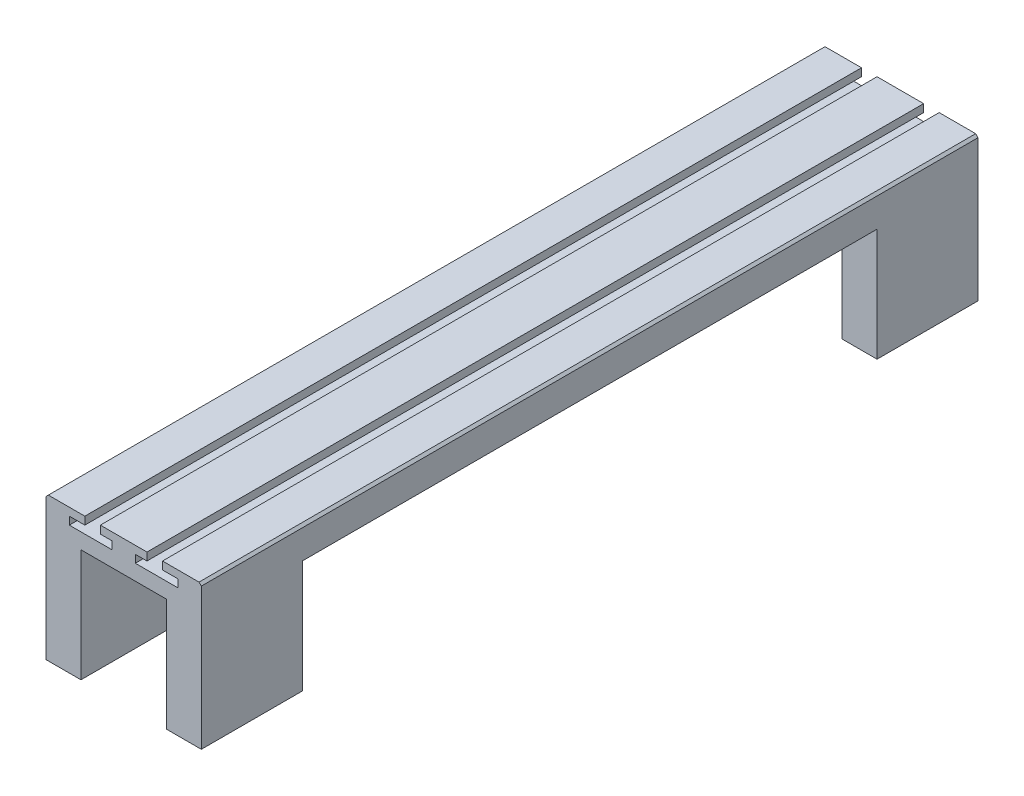
SolidWorks part; units mm, degrees
ref_plane "Front Plane" through (0, 0, 0) normal (0, 0, 1) x (1, 0, 0)
ref_plane "Top Plane" through (0, 0, 0) normal (0, 1, 0) x (1, 0, 0)
ref_plane "Right Plane" through (0, 0, 0) normal (1, 0, 0) x (0, 0, -1)
sketch "Sketch1" plane through (0, 0, 0) normal (0, 0, 1) x (1, 0, 0)
  line L0 (-8.5485, 0) -> (-50, 0)
  line L1 (-50, 0) -> (-50, -40)
  line L2 (-50, -40) -> (150, -40)
  line L3 (150, -40) -> (150, 0)
  line L4 (150, 0) -> (131.4515, 0)
  line L5 (120, -10) -> (120, -20)
  line L6 (120, -20) -> (65, -20)
  line L7 (65, -20) -> (65, -10)
  line L8 (77.4286, 0) -> (47.4286, 0)
  line L9 (35, -10) -> (35, -20)
  line L10 (35, -20) -> (-20, -20)
  line L11 (-20, -20) -> (-20, -10)
  line L12 (131.4515, 0) -> (100, 0)
  line L13 (100, 0) -> (100, -10)
  line L14 (100, -10) -> (120, -10)
  line L15 (77.4286, 0) -> (80, 0)
  line L16 (80, 0) -> (80, -10)
  line L17 (80, -10) -> (65, -10)
  line L18 (47.4286, 0) -> (20, 0)
  line L19 (20, 0) -> (20, -10)
  line L20 (20, -10) -> (35, -10)
  line L21 (-8.5485, 0) -> (0, 0)
  line L22 (0, 0) -> (0, -10)
  line L23 (0, -10) -> (-20, -10)
  line L24 (50, -40) -> (50, 39.4571) construction
  dimension "D1" = 200
  dimension "D2" = 40
  dimension "D3" = 20
  dimension "D4" = 50
  dimension "D5" = 60
  dimension "D6" = 50
  dimension "D7" = 20
  dimension "D8" = 30
  dimension "D9" = 30
  dimension "D10" = 30
  dimension "D11" = 15
  dimension "D12" = 10
extrude "Boss-Extrude1" add sketch "Sketch1" along normal blind 1000
sketch "Sketch2" plane through (0, -40, 0) normal (0, -1, 0) x (1, 0, 0)
  line L0 (50, 1000) -> (50, 0) construction
  line L1 (-50, 1000) -> (150, 1000) construction
  line L2 (-50, 0) -> (150, 0) construction
  line L3 (-50, 500) -> (150, 500) construction
  line L4 (-50, 1000) -> (-50, 0) construction
  line L5 (150, 1000) -> (150, 0) construction
  line L6 (105, 1000) -> (105, 870)
  line L7 (-50, 1000) -> (-5, 1000)
  line L8 (-50, 1000) -> (-50, 870)
  line L9 (-50, 870) -> (-5, 870)
  line L10 (-5, 1000) -> (-5, 870)
  line L11 (150, 870) -> (105, 870)
  line L12 (150, 1000) -> (150, 870)
  line L13 (150, 1000) -> (105, 1000)
  line L14 (150, 0) -> (105, 0)
  line L15 (150, 0) -> (150, 130)
  line L16 (150, 130) -> (105, 130)
  line L17 (105, 0) -> (105, 130)
  line L18 (-50, 130) -> (-5, 130)
  line L19 (-5, 0) -> (-5, 130)
  line L20 (-50, 0) -> (-5, 0)
  line L21 (-50, 0) -> (-50, 130)
  dimension "D1" = 45
  dimension "D2" = 130
extrude "Boss-Extrude2" add sketch "Sketch2" along normal blind 145
chamfer "Chamfer1" distance 3 angle 45 2 edges at (-50, 0, 500) (150, 0, 500)
